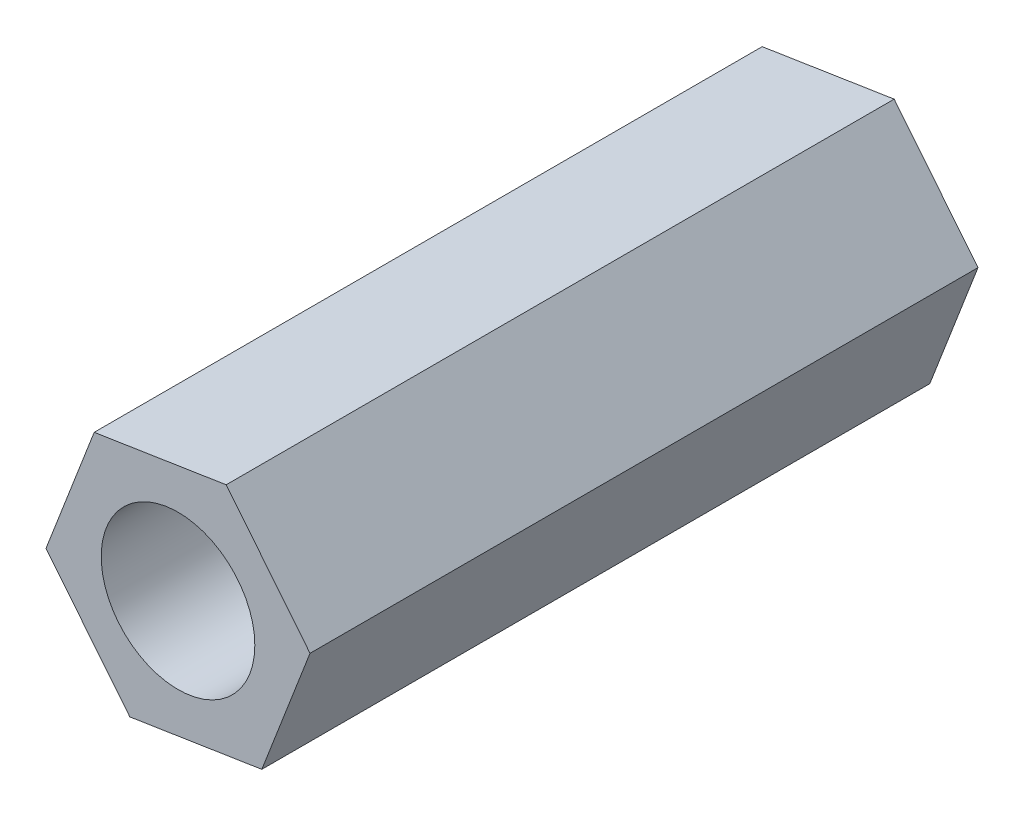
SolidWorks part; units mm, degrees
ref_plane "前视基准面" through (0, 0, 0) normal (0, 0, 1) x (1, 0, 0)
ref_plane "上视基准面" through (0, 0, 0) normal (0, 1, 0) x (1, 0, 0)
ref_plane "右视基准面" through (0, 0, 0) normal (1, 0, 0) x (0, 0, -1)
sketch "草图1" plane through (0, 0, 0) normal (0, 0, 1) x (1, 0, 0)
  line L1 (6.2736, -7.7873) -> (9.8808, 1.5394)
  line L2 (9.8808, 1.5394) -> (3.6072, 9.3267)
  line L3 (3.6072, 9.3267) -> (-6.2736, 7.7873)
  line L4 (-6.2736, 7.7873) -> (-9.8808, -1.5394)
  line L5 (-9.8808, -1.5394) -> (-3.6072, -9.3267)
  line L6 (-3.6072, -9.3267) -> (6.2736, -7.7873)
  circle A0 centre (0, 0) radius 8.6603 construction
  circle A1 centre (0, 0) radius 5.75
  dimension "D2" = 11.5
  dimension "D1" = 20
extrude "凸台-拉伸1" add sketch "草图1" along normal blind 50
hole_wizard "M5 螺纹孔1" positions "草图3" profile "草图2" tap size "M5" standard "GB"
sketch "草图3" plane through (-6.744, -5.4331, 0) normal (-0.7787, -0.6274, 0) x (0, 0, 1)
  line L0 (50, 5) -> (0, 5) construction
  point P0 (9.322, 0)
  dimension "D1" = 5
sketch "草图2" plane through (-6.744, -5.4331, 9.322) normal (0, 0, 1) x (0.6274, -0.7787, 0)
  line L0 (0, 0) -> (0, 13.6618)
  line L1 (0, 13.6618) -> (2.1, 12.4)
  line L2 (2.1, 12.4) -> (2.1, 0)
  line L5 (2.1, 0) -> (0, 0)
  line L10 (0, 13.6618) -> (-2.1, 12.4) construction
  line L11 (0, -6.35) -> (0, 107.95) construction
  dimension "螺纹孔钻头直径" = 4.2
  dimension "螺纹孔钻头深度" = 12.4
  dimension "导头角度" = 118
cosmetic thread "孔螺蚊线1"
